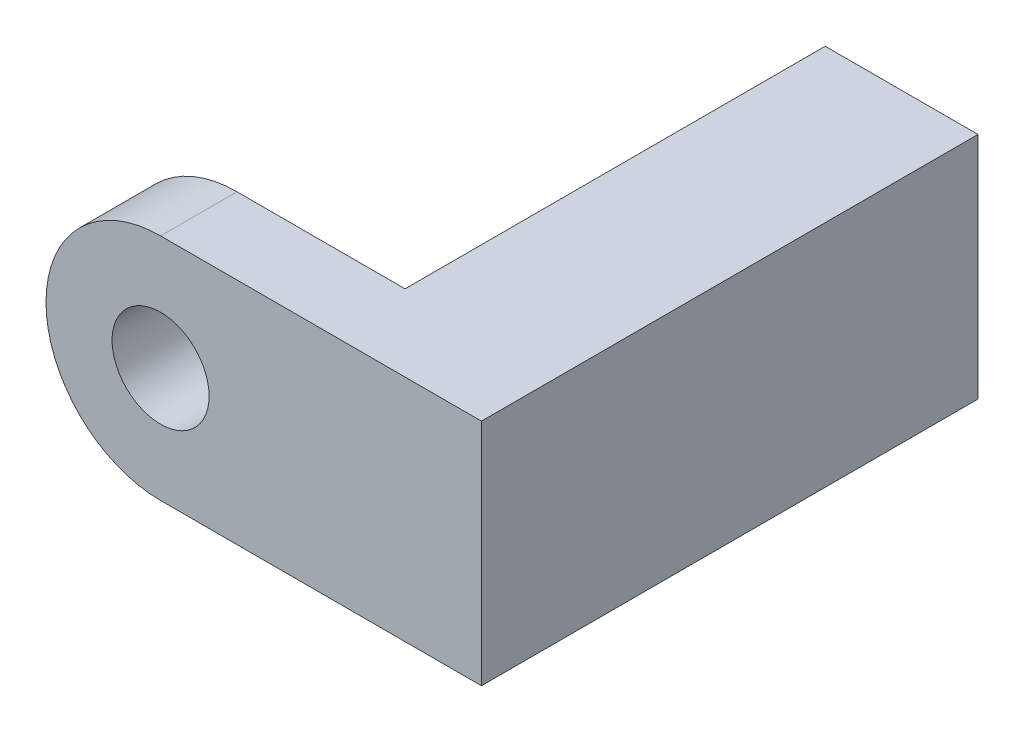
SolidWorks part; units mm, degrees
ref_plane "Front Plane" through (0, 0, 0) normal (0, 0, 1) x (1, 0, 0)
ref_plane "Top Plane" through (0, 0, 0) normal (0, 1, 0) x (1, 0, 0)
ref_plane "Right Plane" through (0, 0, 0) normal (1, 0, 0) x (0, 0, -1)
sketch "Sketch1" plane through (0, 0, 0) normal (0, 0, 1) x (1, 0, 0)
  line L1 (22, 15) -> (42, 15)
  line L2 (22, 15) -> (22, -15)
  line L3 (22, -15) -> (42, -15)
  line L4 (42, 15) -> (42, -15)
  point P4 (42, 0)
  dimension "D1" = 20
  dimension "D2" = 30
  dimension "D3" = 22
extrude "Boss-Extrude1" add sketch "Sketch1" along normal blind 55
sketch "Sketch2" plane through (0, 0, 55) normal (0, 0, 1) x (1, 0, 0)
  line L3 (42, -15) -> (42, 15) construction
  line L4 (42, 15) -> (42, -15)
  line L6 (22, 15) -> (22, -15)
  line L7 (22, -15) -> (42, -15)
  line L8 (42, -15) -> (42, 15)
  line L9 (42, 15) -> (22, 15)
  line L11 (0, -15) -> (42, -15)
  line L13 (42, 15) -> (0, 15)
  arc A0 (0, 15) -> (0, -15) centre (0, 0) ccw
  dimension "D1" = 0
extrude "Boss-Extrude2" add sketch "Sketch2" along normal blind 10
sketch "Sketch3" plane through (0, 0, 65) normal (0, 0, 1) x (1, 0, 0)
  circle A0 centre (0, 0) radius 6.35
  dimension "D1" = 12.7
extrude "Cut-Extrude1" cut sketch "Sketch3" against normal up to surface (10 mm away) up to face at (7.25, 0, 55)
